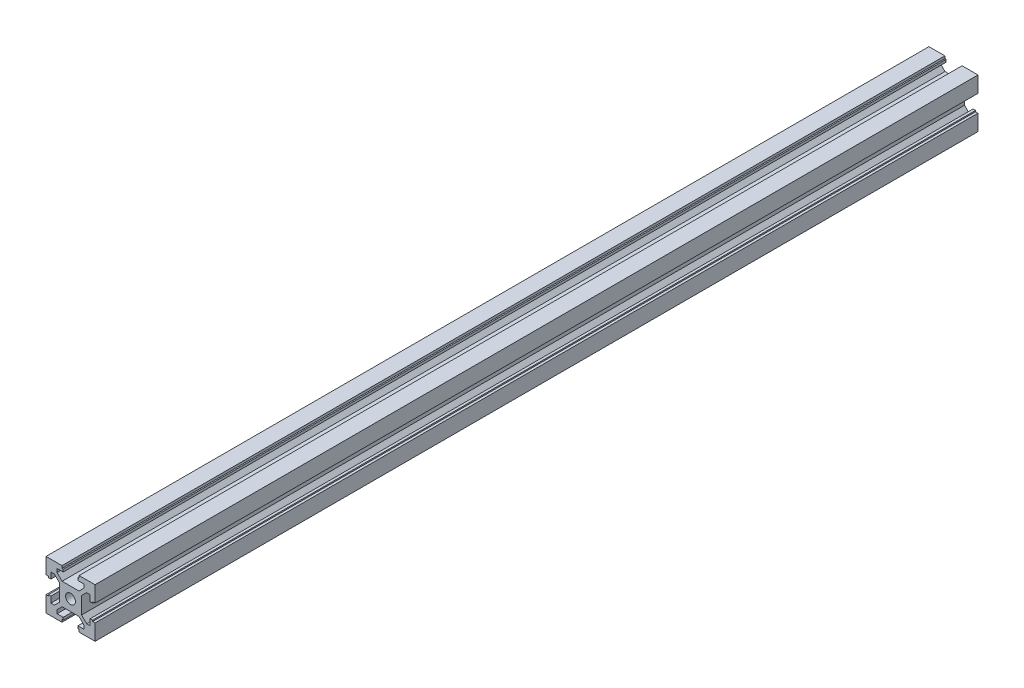
SolidWorks part; units mm, degrees
ref_plane "Front Plane" through (0, 0, 0) normal (0, 0, 1) x (1, 0, 0)
ref_plane "Top Plane" through (0, 0, 0) normal (0, 1, 0) x (1, 0, 0)
ref_plane "Right Plane" through (0, 0, 0) normal (1, 0, 0) x (0, 0, -1)
sketch "Sketch1" plane through (0, 0, 0) normal (0, 0, 1) x (1, 0, 0)
  line L0 (0, 10) -> (0, -4.5007) construction
  line L1 (-10, -10) -> (-3.5, -10)
  line L2 (-10, -10) -> (-10, -3.5)
  line L3 (-10, 10) -> (-3.5, 10)
  line L4 (10, -10) -> (10, -3.5)
  line L5 (-10, -10) -> (10, 10) construction
  line L6 (-10, 10) -> (10, -10) construction
  line L7 (-10, 0) -> (10, 0) construction
  line L8 (-3.5, 10) -> (-3.5, 9)
  line L9 (-3.44, -4.5007) -> (3.44, -4.5007)
  line L10 (-4.5007, -3.44) -> (-4.5007, 3.44)
  line L11 (-3.44, 4.5007) -> (3.44, 4.5007)
  line L12 (4.5007, -3.44) -> (4.5007, 3.44)
  line L13 (-10, -10) -> (10, 10) construction
  line L14 (-10, 10) -> (10, -10) construction
  line L15 (-3.5, 9) -> (-3, 9)
  line L16 (-3, 9) -> (-3, 8)
  line L17 (-3, 8) -> (-5.5, 8)
  line L18 (-5.5, 8) -> (-5.5, 6.5607)
  line L19 (-5.5, 6.5607) -> (-3.44, 4.5007)
  line L20 (3.5, 10) -> (10, 10)
  line L21 (3.5, 9) -> (3, 9)
  line L22 (5.5, 6.5607) -> (3.44, 4.5007)
  line L23 (5.5, 8) -> (5.5, 6.5607)
  line L24 (3, 8) -> (5.5, 8)
  line L25 (3, 9) -> (3, 8)
  line L26 (3.5, 10) -> (3.5, 9)
  line L27 (-3.5, 10) -> (3.5, 10) construction
  line L28 (5.5, -6.5607) -> (3.44, -4.5007)
  line L29 (5.5, -8) -> (5.5, -6.5607)
  line L30 (3, -8) -> (5.5, -8)
  line L31 (3, -9) -> (3, -8)
  line L32 (3.5, -9) -> (3, -9)
  line L33 (3.5, -10) -> (3.5, -9)
  line L34 (-3.5, -9) -> (-3, -9)
  line L35 (-5.5, -6.5607) -> (-3.44, -4.5007)
  line L36 (-5.5, -8) -> (-5.5, -6.5607)
  line L37 (-3, -8) -> (-5.5, -8)
  line L38 (-3, -9) -> (-3, -8)
  line L39 (-3.5, -10) -> (-3.5, -9)
  line L40 (-6.5607, -5.5) -> (-4.5007, -3.44)
  line L41 (-8, -5.5) -> (-6.5607, -5.5)
  line L42 (-8, -3) -> (-8, -5.5)
  line L43 (-10, -3.5) -> (-9, -3.5)
  line L44 (-9, -3) -> (-8, -3)
  line L45 (-9, -3.5) -> (-9, -3)
  line L46 (6.5607, -5.5) -> (4.5007, -3.44)
  line L47 (8, -5.5) -> (6.5607, -5.5)
  line L48 (8, -3) -> (8, -5.5)
  line L49 (9, -3) -> (8, -3)
  line L50 (9, -3.5) -> (9, -3)
  line L51 (10, -3.5) -> (9, -3.5)
  line L52 (-6.5607, 5.5) -> (-4.5007, 3.44)
  line L53 (-8, 5.5) -> (-6.5607, 5.5)
  line L54 (-8, 3) -> (-8, 5.5)
  line L55 (-9, 3) -> (-8, 3)
  line L56 (-9, 3.5) -> (-9, 3)
  line L57 (-10, 3.5) -> (-9, 3.5)
  line L58 (10, 3.5) -> (9, 3.5)
  line L59 (9, 3.5) -> (9, 3)
  line L60 (9, 3) -> (8, 3)
  line L61 (8, 3) -> (8, 5.5)
  line L62 (8, 5.5) -> (6.5607, 5.5)
  line L63 (6.5607, 5.5) -> (4.5007, 3.44)
  line L64 (10, 3.5) -> (10, 10)
  line L65 (-10, 3.5) -> (-10, 10)
  line L66 (-10, 3.5) -> (-10, -3.5) construction
  line L67 (10, 3.5) -> (10, -3.5) construction
  line L68 (3.5, -10) -> (10, -10)
  line L69 (-3.5, -10) -> (3.5, -10) construction
  circle A0 centre (0, 0) radius 2
  point P0 (0, 0)
  point P10 (0, 0)
  dimension "D10" = 4
  dimension "D1" = 20
  dimension "D2" = 14.5007
  dimension "D3" = 0.75
  dimension "D4" = 3.5
  dimension "D5" = 3
  dimension "D6" = 1
  dimension "D7" = 1
  dimension "D8" = 3.44
  dimension "D9" = 5.5
extrude "Boss-Extrude1" add sketch "Sketch1" along normal blind 360
